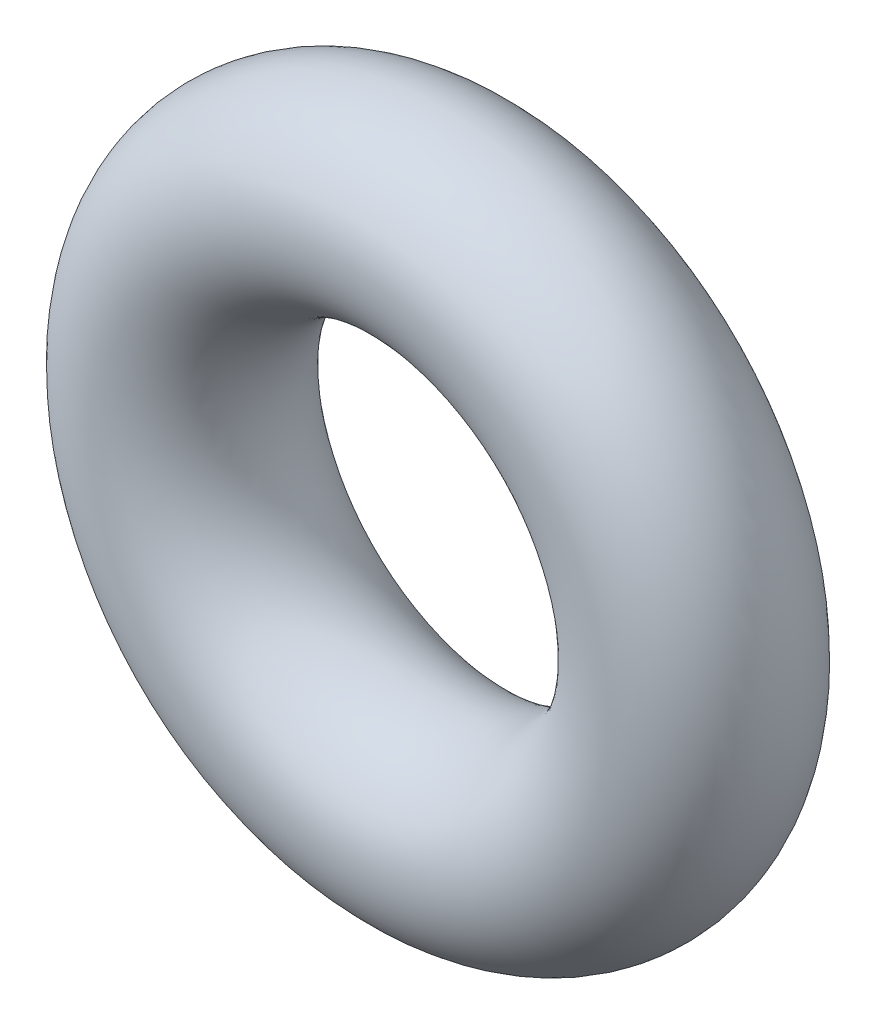
SolidWorks part; units mm, degrees
ref_plane "Front Plane" through (0, 0, 0) normal (0, 0, 1) x (1, 0, 0)
ref_plane "Top Plane" through (0, 0, 0) normal (0, 1, 0) x (1, 0, 0)
ref_plane "Right Plane" through (0, 0, 0) normal (1, 0, 0) x (0, 0, -1)
sketch "Sketch1" plane through (0, 0, 0) normal (0, 0, 1) x (1, 0, 0)
  line L0 (-2.75, 0) -> (2.75, 0) construction
  circle A0 centre (0, 0) radius 2.75
  circle A1 centre (0, 0) radius 1.25
  point P4 (1.25, 0)
  point P5 (2.75, 0)
  point P8 (0, 0)
  dimension "ID" = 2.5
  dimension "Width" = 1.5
  dimension "OD" = 5.5
sketch "Sketch2" plane through (0, 0, 0) normal (0, 1, 0) x (1, 0, 0)
  line L0 (-2.75, 0) -> (2.75, 0) construction
  line L1 (0, 0.75) -> (0, -0.75) construction
  circle A0 centre (2, 0) radius 0.75
  point P8 (0, 0)
  point P11 (2, 0.75)
revolve "Revolve1" add sketch "Sketch2" angle 360 about L1
sketch "Sketch3" plane through (0, 0, 0) normal (1, 0, 0) x (0, 0, -1)
  line L0 (-0.75, 0) -> (0.75, 0) construction
  line L1 (0.75, -2) -> (0.75, 2) construction
  point P2 (0, 0)
